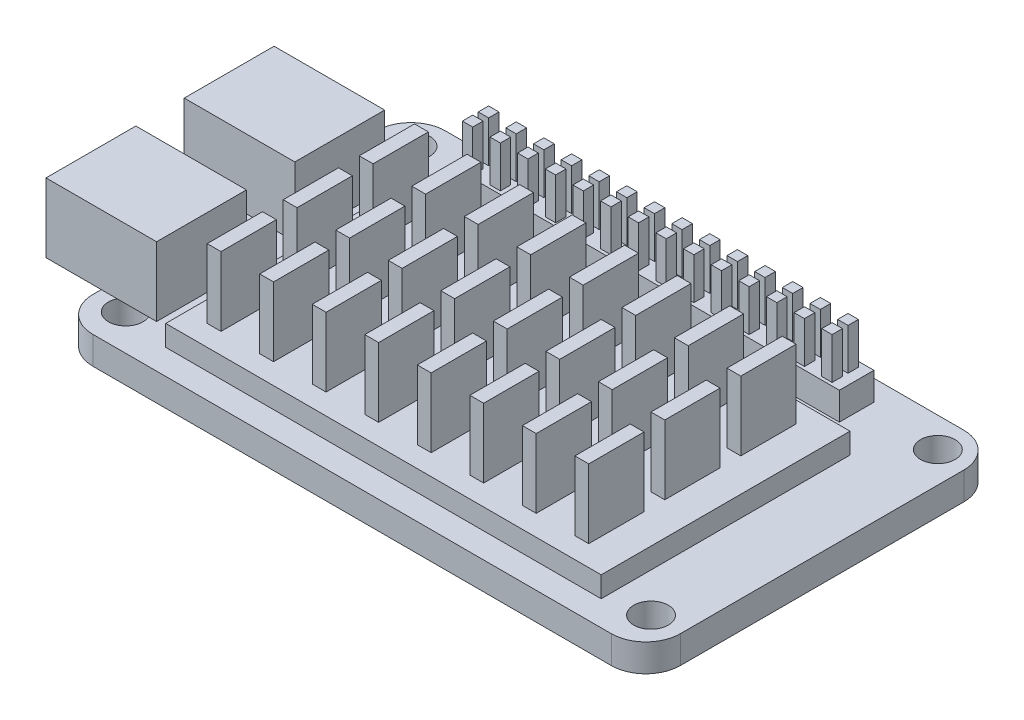
SolidWorks part; units mm, degrees
ref_plane "Front Plane" through (0, 0, 0) normal (0, 0, 1) x (1, 0, 0)
ref_plane "Top Plane" through (0, 0, 0) normal (0, 1, 0) x (1, 0, 0)
ref_plane "Right Plane" through (0, 0, 0) normal (1, 0, 0) x (0, 0, -1)
sketch "Sketch1" plane through (0, 0, 0) normal (0, 1, 0) x (1, 0, 0)
  line L1 (5, 0) -> (80, 0)
  line L2 (0, -5) -> (0, -46)
  line L3 (5, -51) -> (80, -51)
  line L4 (85, -5) -> (85, -46)
  arc A0 (0, -46) -> (5, -51) centre (5, -46) ccw
  arc A1 (80, -51) -> (85, -46) centre (80, -46) ccw
  arc A2 (80, 0) -> (85, -5) centre (80, -5) cw
  arc A3 (5, 0) -> (0, -5) centre (5, -5) ccw
  point P7 (0, -51)
  point P12 (85, 0)
  point P15 (0, 0)
  dimension "D3" = 5
  dimension "D1" = 85
  dimension "D2" = 51
extrude "Boss-Extrude1" add sketch "Sketch1" along normal blind 4
sketch "Sketch3" plane through (0, 4, 0) normal (0, 1, 0) x (1, 0, 0)
  circle A0 centre (4.556, -4.3057) radius 2.5
  dimension "D1" = 5
extrude "Cut-Extrude1" cut sketch "Sketch3" against normal blind 4
pattern_linear "LPattern1" count 2 spacing 76 along (1, 0, 0) count 2 spacing 41.5 along (0, 0, 1) of "Cut-Extrude1"
sketch "Sketch4" plane through (0, 4, 0) normal (0, 1, 0) x (1, 0, 0)
  line L0 (80, 0) -> (5, 0) construction
  line L1 (14, -3) -> (70, -3)
  line L2 (14, -3) -> (14, -8)
  line L3 (14, -8) -> (70, -8)
  line L4 (70, -3) -> (70, -8)
  line L5 (0, -5) -> (0, -46) construction
  dimension "D1" = 5
  dimension "D2" = 56
  dimension "D3" = 3
  dimension "D4" = 14
extrude "Boss-Extrude2" add sketch "Sketch4" along normal blind 4
sketch "Sketch5" plane through (0, 8, 0) normal (0, 1, 0) x (1, 0, 0)
  line L0 (70, -3) -> (14, -3) construction
  line L1 (15, -3.75) -> (16.5, -3.75)
  line L2 (15, -3.75) -> (15, -5.25)
  line L3 (15, -5.25) -> (16.5, -5.25)
  line L4 (16.5, -3.75) -> (16.5, -5.25)
  line L5 (14, -3) -> (14, -8) construction
  dimension "D1" = 1.5
  dimension "D2" = 1.5
  dimension "D3" = 0.75
  dimension "D4" = 1
extrude "Boss-Extrude3" add sketch "Sketch5" along normal blind 6
pattern_linear "LPattern2" count 14 spacing 4 along (1, 0, 0) count 2 spacing 2.3 along (0, 0, 1) of "Boss-Extrude3"
sketch "Sketch6" plane through (0, 0, 0) normal (1, 0, 0) x (0, 0, -1)
  line L0 (-46, 4) -> (-5, 4) construction
  line L1 (-44.7855, 4) -> (-31.7855, 4)
  line L2 (-44.7855, 4) -> (-44.7855, 14)
  line L3 (-44.7855, 14) -> (-31.7855, 14)
  line L4 (-31.7855, 4) -> (-31.7855, 14)
  dimension "D1" = 13
  dimension "D2" = 10
extrude "usb hub" add sketch "Sketch6" along normal mid plane 16
sketch "Sketch7" plane through (-8, 0, 0) normal (-1, 0, 0) x (0, 0, 1)
  line L0 (31.7855, 4) -> (31.7855, 14) construction
  line L1 (32.2855, 13.5685) -> (44.2855, 13.5685)
  line L2 (32.2855, 13.5685) -> (32.2855, 9.0685)
  line L3 (32.2855, 9.0685) -> (44.2855, 9.0685)
  line L4 (44.2855, 13.5685) -> (44.2855, 9.0685)
  line L5 (32.2855, 8.7685) -> (44.2855, 8.7685)
  line L6 (32.2855, 8.7685) -> (32.2855, 4.2685)
  line L7 (32.2855, 4.2685) -> (44.2855, 4.2685)
  line L8 (44.2855, 8.7685) -> (44.2855, 4.2685)
  dimension "D1" = 12
  dimension "D2" = 4.5
  dimension "D3" = 12
  dimension "D4" = 4.5
  dimension "D5" = 0.5
  dimension "D6" = 0.5
  dimension "D7" = 0.3
extrude "usb" cut sketch "Sketch7" against normal blind 12
pattern_linear "usb hub pattern" count 2 spacing 20 along (0, 0, -1) of "usb hub", "usb"
sketch "Sketch8" plane through (0, 4, 0) normal (0, 1, 0) x (1, 0, 0)
  line L1 (11.8962, -11.3582) -> (74.8962, -11.3582)
  line L2 (11.8962, -11.3582) -> (11.8962, -47.3582)
  line L3 (11.8962, -47.3582) -> (74.8962, -47.3582)
  line L4 (74.8962, -11.3582) -> (74.8962, -47.3582)
  dimension "D1" = 36
  dimension "D2" = 63
extrude "Heat Sink Body" add sketch "Sketch8" along normal blind 3
sketch "Sketch9" plane through (0, 7, 0) normal (0, 1, 0) x (1, 0, 0)
  line L0 (74.8962, -11.3582) -> (11.8962, -11.3582) construction
  line L1 (14.8962, -14.3582) -> (16.8962, -14.3582)
  line L2 (14.8962, -14.3582) -> (14.8962, -22.3582)
  line L3 (14.8962, -22.3582) -> (16.8962, -22.3582)
  line L4 (16.8962, -14.3582) -> (16.8962, -22.3582)
  line L5 (14.8962, -25.3582) -> (16.8962, -25.3582)
  line L6 (14.8962, -25.3582) -> (14.8962, -33.3582)
  line L7 (14.8962, -33.3582) -> (16.8962, -33.3582)
  line L8 (16.8962, -25.3582) -> (16.8962, -33.3582)
  line L9 (14.8962, -36.3582) -> (16.8962, -36.3582)
  line L10 (14.8962, -36.3582) -> (14.8962, -44.3582)
  line L11 (14.8962, -44.3582) -> (16.8962, -44.3582)
  line L12 (16.8962, -36.3582) -> (16.8962, -44.3582)
  line L13 (11.8962, -47.3582) -> (74.8962, -47.3582) construction
  line L14 (11.8962, -11.3582) -> (11.8962, -47.3582) construction
  point P16 (15.8962, -22.3582)
  point P19 (14.8962, -29.3582)
  dimension "D1" = 8
  dimension "D2" = 8
  dimension "D3" = 8
  dimension "D4" = 3
  dimension "D5" = 3
  dimension "D6" = 3
  dimension "D7" = 2
  dimension "D8" = 2
  dimension "D9" = 2
  dimension "D10" = 3
  dimension "D11" = 3
  dimension "D12" = 3
extrude "Heat Sink Sticks" add sketch "Sketch9" along normal blind 10
pattern_linear "heat sink stick pattern" count 8 spacing 7.6 along (1, 0, 0) of "Heat Sink Sticks"
